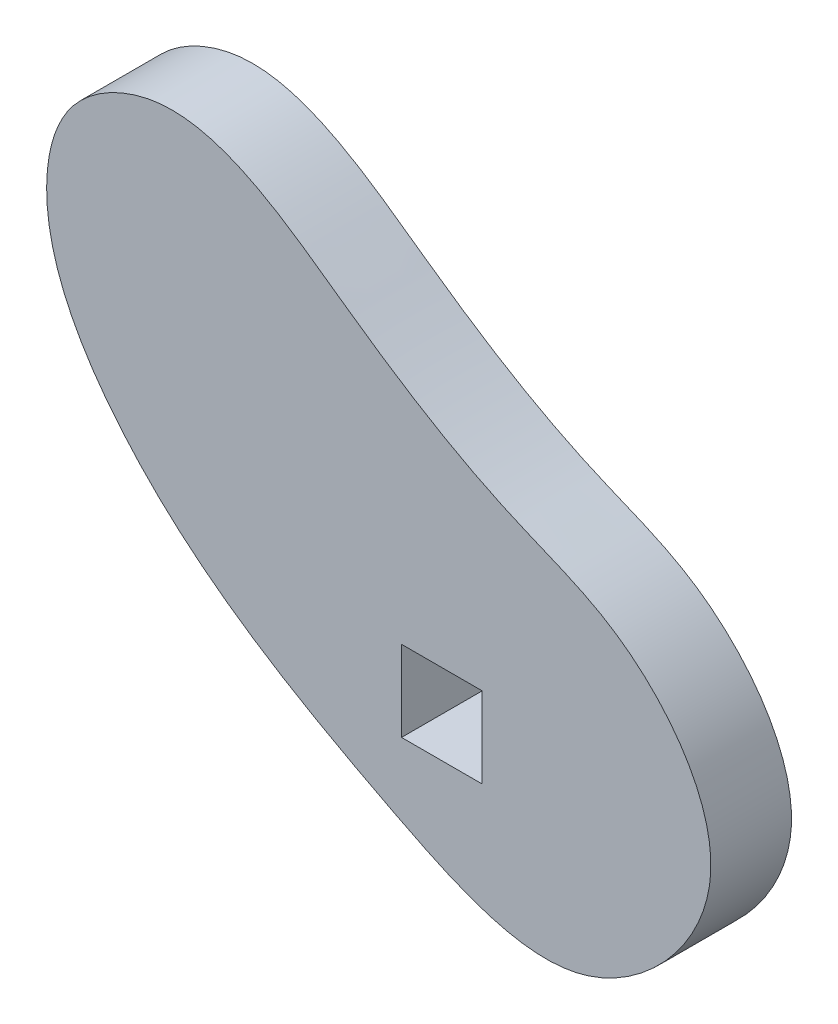
SolidWorks part; units mm, degrees
ref_plane "Front Plane" through (0, 0, 0) normal (0, 0, 1) x (1, 0, 0)
ref_plane "Top Plane" through (0, 0, 0) normal (0, 1, 0) x (1, 0, 0)
ref_plane "Right Plane" through (0, 0, 0) normal (1, 0, 0) x (0, 0, -1)
sketch "Sketch1" plane through (0, 0, 0) normal (0, 0, 1) x (1, 0, 0)
  line L0 (0.7962, 49.6157) -> (0.7962, 48.0917)
  line L1 (0.7962, 48.0917) -> (2.3202, 48.0917)
  line L2 (2.3202, 48.0917) -> (2.3202, 49.6157)
  line L3 (2.3202, 49.6157) -> (0.7962, 49.6157)
  spline S0 degree 3 poles (4.2901, 45.005) (-0.322, 47.2183) (-4.0384, 49.3892) (-6.1554, 52.8979) (-5.724, 55.4222) (-3.1009, 56.7941) (-0.2363, 54.5007) (2.4382, 52.8477) (5.3404, 51.8374) (7.6411, 48.718) (4.2901, 45.005) (-0.322, 47.2183) (-4.0384, 49.3892) knots -0.322789 -0.217256 -0.10736 0 0.187161 0.282081 0.339122 0.39125 0.510585 0.617524 0.677211 0.782744 0.89264 1 1.187161 1.282081 1.339122 only from (0.6609, 46.7856) to (0.6609, 46.7856)
extrude "Boss-Extrude1" add sketch "Sketch1" along normal blind 1.524
